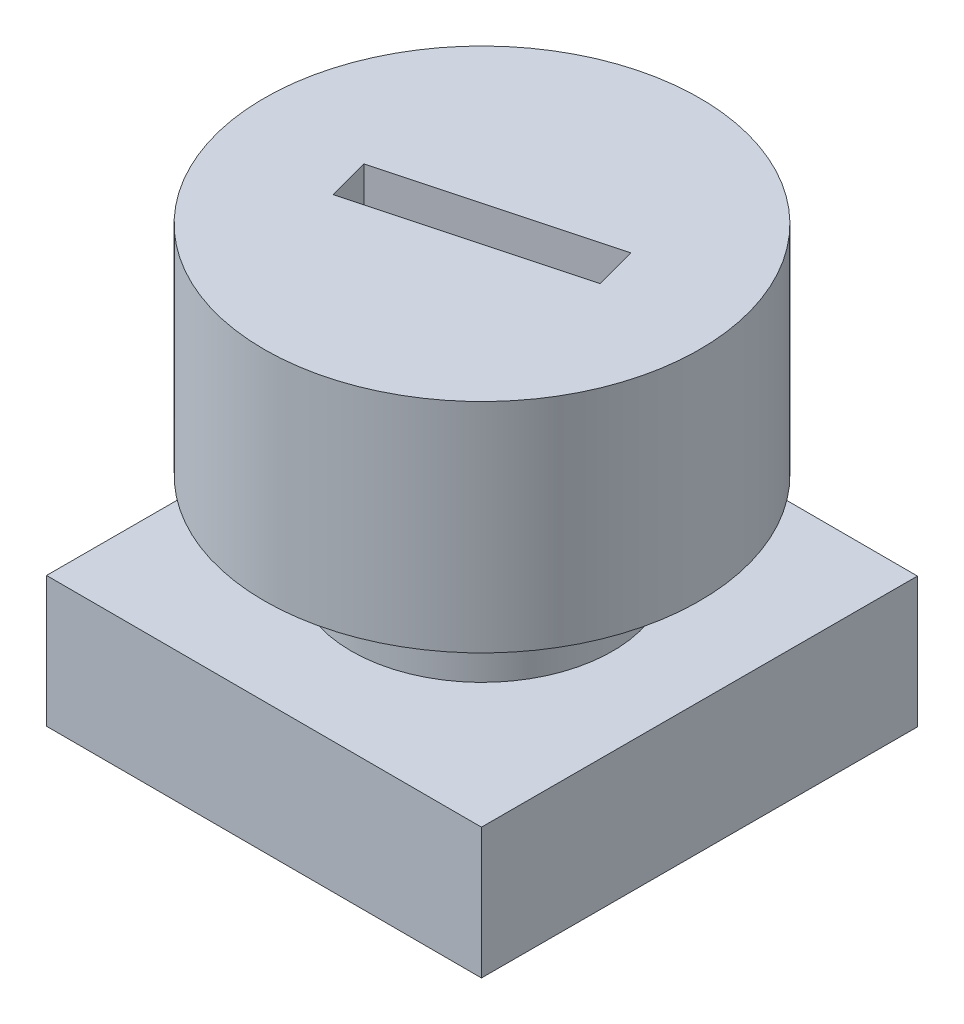
SolidWorks part; units mm, degrees
ref_plane "前视基准面" through (0, 0, 0) normal (0, 0, 1) x (1, 0, 0)
ref_plane "上视基准面" through (0, 0, 0) normal (0, 1, 0) x (1, 0, 0)
ref_plane "右视基准面" through (0, 0, 0) normal (1, 0, 0) x (0, 0, -1)
sketch "草图1" plane through (0, 0, 0) normal (0, 1, 0) x (1, 0, 0)
  circle A0 centre (0, 0) radius 5
  dimension "D1" = 10
extrude "凸台-拉伸1" add sketch "草图1" along normal blind 5
sketch "草图3" plane through (0, 0, 0) normal (0, -1, 0) x (1, 0, 0)
  circle A0 centre (0, 0) radius 3
  dimension "D1" = 6
extrude "凸台-拉伸2" add sketch "草图3" along normal blind 2
sketch "草图4" plane through (0, -2, 0) normal (0, -1, 0) x (1, 0, 0)
  line L1 (4.9937, 5.0063) -> (-5.0063, 4.9937)
  line L2 (-5.0063, 4.9937) -> (-4.9937, -5.0063)
  line L3 (-4.9937, -5.0063) -> (5.0063, -4.9937)
  line L4 (5.0063, -4.9937) -> (4.9937, 5.0063)
  circle A0 centre (0, 0) radius 5 construction
  dimension "D1" = 10
extrude "凸台-拉伸3" add sketch "草图4" along normal blind 3
sketch "草图5" plane through (0, -5, 0) normal (0, -1, 0) x (1, 0, 0)
  circle A0 centre (0, 0) radius 2.5
  point P6 (0, 0)
  dimension "D1" = 5
extrude "切除-拉伸2" cut sketch "草图5" against normal blind 6
sketch "草图2" plane through (0, 5, 0) normal (0, 1, 0) x (1, 0, 0)
  line L0 (-2.7896, -0.7475) -> (5.1852, 1.3894) construction
  line L1 (-2.2854, -1.13) -> (2.5442, 0.1641)
  line L2 (-2.2854, -1.13) -> (-2.5442, -0.1641)
  line L3 (-2.5442, -0.1641) -> (2.2854, 1.13)
  line L4 (2.5442, 0.1641) -> (2.2854, 1.13)
  line L5 (-2.2854, -1.13) -> (2.2854, 1.13) construction
  line L6 (-2.5442, -0.1641) -> (2.5442, 0.1641) construction
  line L7 (0, 0) -> (0, 5.8804) construction
  point P0 (0, 0)
  point P8 (4.2911, 4.2803)
  point P12 (0, 0)
  point P13 (2.9357, 4.4943)
  dimension "D1" = 5
  dimension "D2" = 1
  dimension "D3" = 75
extrude "切除-拉伸1" cut sketch "草图2" against normal blind 3
